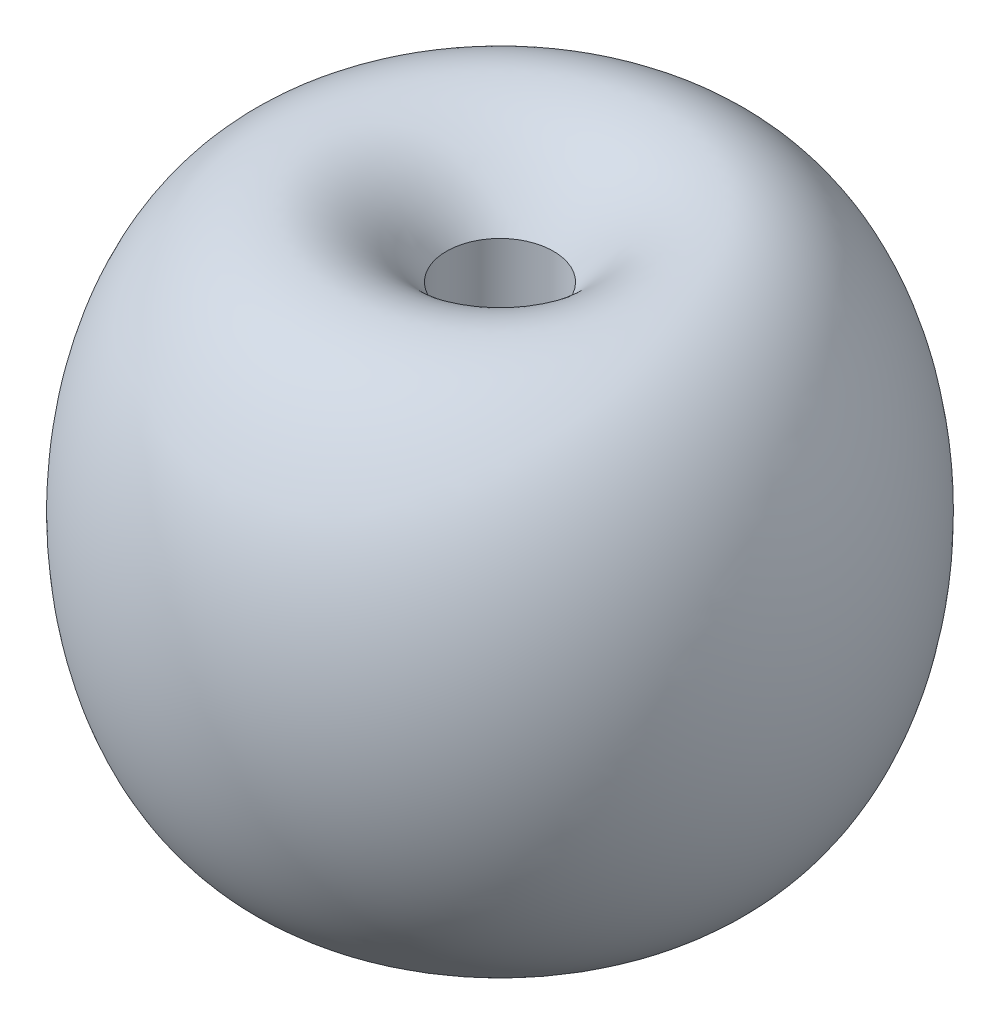
SolidWorks part; units mm, degrees
material "Natural Rubber"
ref_plane "Front Plane" through (0, 0, 0) normal (0, 0, 1) x (1, 0, 0)
ref_plane "Top Plane" through (0, 0, 0) normal (0, 1, 0) x (1, 0, 0)
ref_plane "Right Plane" through (0, 0, 0) normal (1, 0, 0) x (0, 0, -1)
sketch "Sketch1" plane through (0, 0, 0) normal (0, 0, 1) x (1, 0, 0)
  line L0 (0, 30) -> (0, -30) construction
  line L1 (0, 0) -> (-15, 0) construction
  line L4 (0, 16.7089) -> (-5, 16.7089) construction
  line L5 (-5, 18.6339) -> (-5, -18.6339)
  ellipse E0 centre (-15, 0) end of major axis (-15, 25) minor radius 15 (-5, 18.6339) -> (-5, -18.6339) ccw
  point P4 (0, 0)
  dimension "D1" = 15
  dimension "D3" = 25
  dimension "D4" = 5
revolve "apple" add sketch "Sketch1" angle 360 about L0
